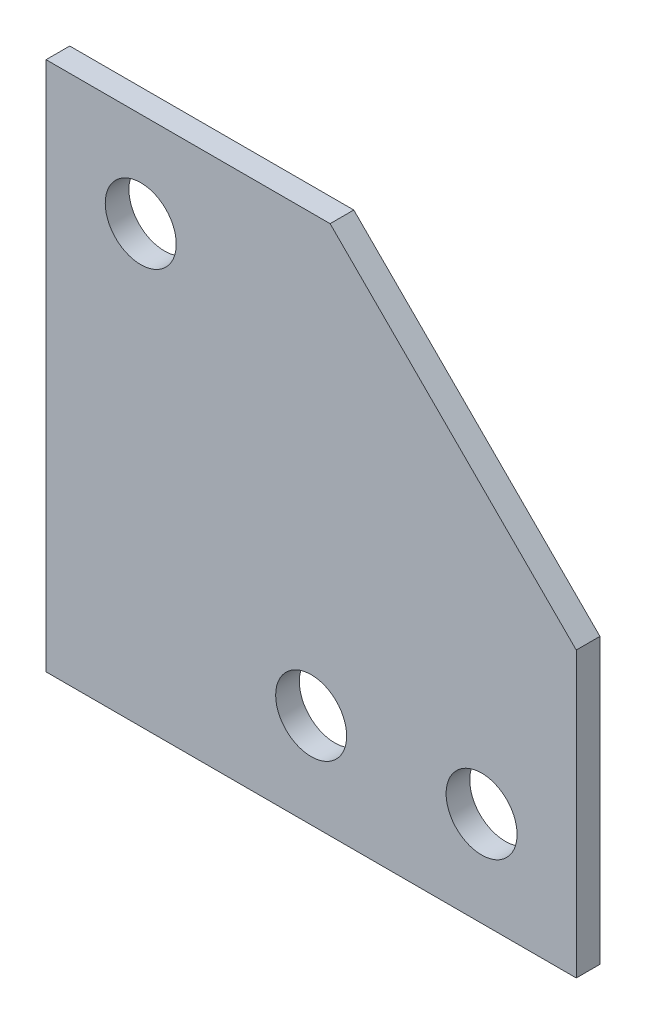
SolidWorks part; units mm, degrees
ref_plane "Front Plane" through (0, 0, 0) normal (0, 0, 1) x (1, 0, 0)
ref_plane "Top Plane" through (0, 0, 0) normal (0, 1, 0) x (1, 0, 0)
ref_plane "Right Plane" through (0, 0, 0) normal (1, 0, 0) x (0, 0, -1)
sketch "Sketch1" plane through (0, 0, 0) normal (0, 0, 1) x (1, 0, 0)
  line L0 (19.05, 0) -> (35.56, -16.51)
  line L1 (0, 0) -> (19.05, 0)
  line L2 (0, 0) -> (0, -35.56)
  line L3 (0, -35.56) -> (35.56, -35.56)
  line L5 (35.56, -16.51) -> (35.56, -35.56)
  point P5 (6.35, -29.21)
  point P7 (17.78, -29.21)
  point P8 (29.21, -29.21)
  point P9 (6.35, -6.35)
  dimension "D1" = 35.56
  dimension "D2" = 35.56
  dimension "D3" = 19.05
  dimension "D4" = 19.05
  dimension "D5" = 6.35
  dimension "D6" = 6.35
  dimension "D7" = 6.35
  dimension "D8" = 17.78
  dimension "D9" = 6.35
  dimension "D10" = 6.35
  dimension "D11" = 6.35
  dimension "D12" = 6.35
extrude "Boss-Extrude1" add sketch "Sketch1" along normal blind 1.5875
hole_wizard "3/16 (0.1875) Diameter Hole1" positions "Sketch2" profile "Sketch3" hole size "3/16" standard "ANSI Inch" end condition through all
sketch "Sketch2" plane through (0, 0, 0) normal (0, 0, -1) x (-1, 0, 0)
  point P3 (-6.35, -6.35)
  point P9 (-17.78, -29.21)
  point P12 (-29.21, -29.21)
  point P15 (0, 0)
sketch "Sketch3" plane through (6.35, -6.35, 0) normal (1, 0, 0) x (0, 1, 0)
  line L0 (0, 0) -> (0, 1.5875)
  line L1 (0, 1.5875) -> (2.3812, 1.5875)
  line L2 (2.3812, 1.5875) -> (2.3812, 0)
  line L5 (2.3812, 0) -> (0, 0)
  line L11 (0, -6.35) -> (0, 107.95) construction
  dimension "Thru Hole Dia." = 4.7625
  dimension "Thru Hole Depth" = 1.5875
